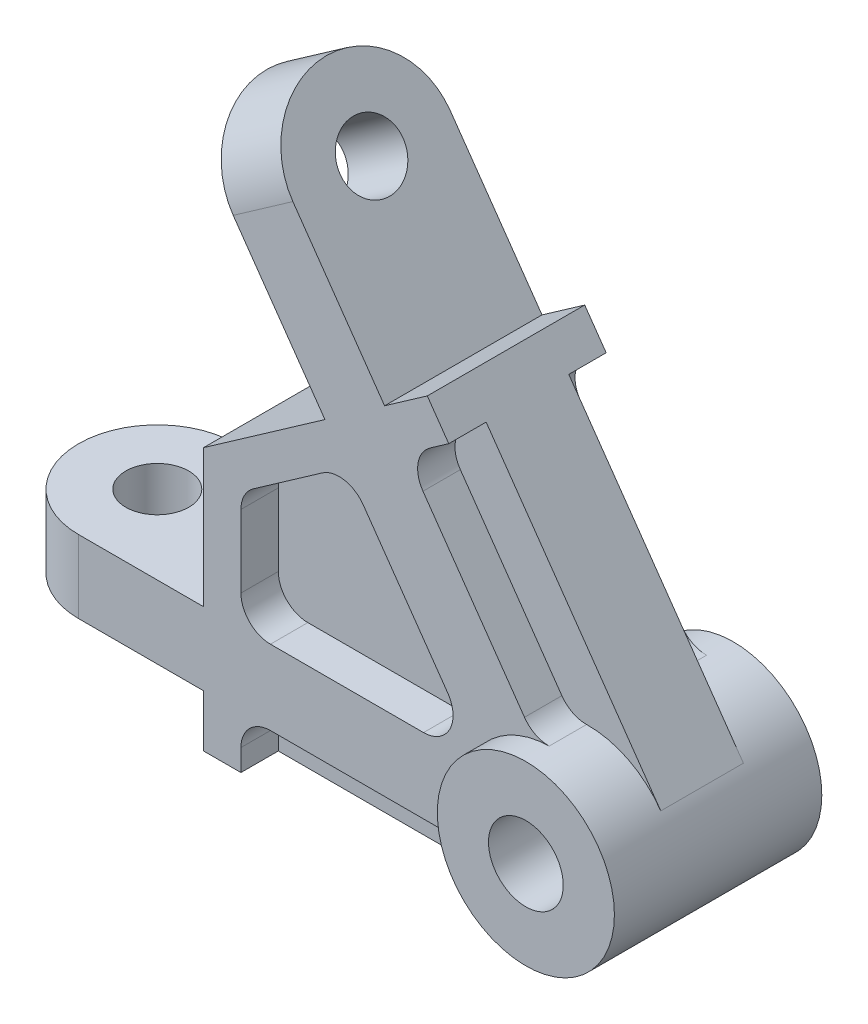
SolidWorks part; units mm, degrees
material "1060 Alloy"
ref_plane "Front Plane" through (0, 0, 0) normal (0, 0, 1) x (1, 0, 0)
ref_plane "Top Plane" through (0, 0, 0) normal (0, 1, 0) x (1, 0, 0)
ref_plane "Right Plane" through (0, 0, 0) normal (1, 0, 0) x (0, 0, -1)
sketch "Sketch2" plane through (0, 0, 0) normal (0, 1, 0) x (1, 0, 0)
  line L0 (0, 0) -> (-120, 0) construction
  line L1 (0, -20) -> (-120, -20)
  line L2 (0, 20) -> (-120, 20)
  line L3 (0, 30.8495) -> (0, -33.8206) construction
  line L4 (0, 20) -> (0, -20)
  circle A0 centre (-120, 0) radius 8
  arc A1 (-120, 20) -> (-120, -20) centre (-120, 0) ccw
  point P2 (0, 0)
  dimension "D3" = 16
  dimension "D1" = 40
  dimension "D2" = 120
extrude "Boss-Extrude1" add sketch "Sketch2" along normal mid plane 18.5
ref_plane "Plane1" through (0, 0, 0) normal (0.8192, 0.5736, 0) x (0.5736, -0.8192, 0)
sketch "Sketch3" plane through (0, 0, 0) normal (0.8192, 0.5736, 0) x (0.5736, -0.8192, 0)
  line L0 (0, 0) -> (-127.5, 0) construction
  line L1 (0, -20) -> (-127.5, -20)
  line L2 (0, 20) -> (-127.5, 20)
  line L3 (0, 20) -> (0, -20)
  arc A0 (127.5, -20) -> (127.5, 20) centre (127.5, 0) ccw
  arc A1 (-127.5, 20) -> (-127.5, -20) centre (-127.5, 0) ccw
  circle A2 centre (-127.5, 0) radius 8
  point P2 (0, 0)
  dimension "D2" = 16
  dimension "D1" = 40
  dimension "Achange" = 127.5
extrude "Boss-Extrude2" add sketch "Sketch3" along normal mid plane 18.5
sketch "Sketch5" plane through (0, 0, 0) normal (0, 0, 1) x (1, 0, 0)
  line L0 (0, -22.5) -> (-88.25, -22.5)
  line L1 (18.4309, 12.9055) -> (-31.3931, 84.0616)
  line L2 (-88.25, -22.5) -> (-88.25, 44.25)
  line L3 (-120, 9.25) -> (-17.7691, 9.25) construction
  line L4 (-88.25, 44.25) -> (-31.3931, 84.0616)
  line L5 (12.6187, -18.0213) -> (-12.6187, 18.0213) construction
  circle A0 centre (0, 0) radius 22.5
  dimension "D1" = 45
  dimension "D2" = 31.75
  dimension "D3" = 35
extrude "Boss-Extrude3" add sketch "Sketch5" along normal mid plane 40 contours A0 L1 L4 L2 L0 | A0
sketch "Sketch6" plane through (0, 0, 0) normal (0, 0, 1) x (1, 0, 0)
  circle A0 centre (0, 0) radius 9.5
  dimension "D1" = 19
extrude "Cut-Extrude1" cut sketch "Sketch6" against normal mid plane 40
sketch "Sketch7" plane through (0, 0, 20) normal (0, 0, 1) x (1, 0, 0)
  line L0 (18.4309, 12.9055) -> (-31.3931, 84.0616) construction
  line L1 (-36.7979, 68.6798) -> (-25.9442, 76.2797)
  line L2 (-36.7979, 68.6798) -> (-4.1873, 22.1069)
  line L3 (-42.2469, 76.4617) -> (-65.5538, 109.7475) construction
  line L4 (-51.9522, 58.0686) -> (-26.1829, 21.2662)
  line L5 (-57.4012, 65.8506) -> (-80.7082, 99.1363) construction
  line L6 (-26.1829, 21.2662) -> (-17.9441, 9.5)
  line L7 (0, 9.5) -> (-120, 9.5)
  line L8 (-36.7979, 9.5) -> (-78.75, 9.5)
  line L9 (0, -9.5) -> (-120, -9.5)
  line L10 (-20.3961, -9.5) -> (-78.75, -9.5)
  line L11 (-36.7979, 9.5) -> (-17.9441, 9.5)
  line L12 (-78.75, -22.5) -> (-78.75, -9.25)
  line L13 (-78.75, -22.5) -> (-78.75, -9.25)
  line L14 (-25.9442, 76.2797) -> (18.4309, 12.9055)
  line L15 (-78.75, -22.5) -> (0, -22.5)
  line L23 (-78.75, 9.25) -> (-78.75, 39.3046)
  line L24 (-78.75, 39.3046) -> (-51.9522, 58.0686)
  line L25 (-78.75, 9.25) -> (-78.75, 39.3046)
  line L26 (-78.75, 39.3046) -> (-51.9522, 58.0686)
  arc A0 (-20.3961, -9.5) -> (-4.1873, 22.1069) centre (0, 0) ccw
  arc A1 (0, -22.5) -> (18.4309, 12.9055) centre (0, 0) ccw construction
  dimension "D1" = 9.5
  dimension "D2" = 9.5
  dimension "D3" = 9.5
  dimension "D4" = 9.5
extrude "Cut-Extrude3" cut sketch "Sketch7" against normal blind 9.5 contours L26 L25 L8 L11 L6 L4 | A0 L5 L1 L2 | A0 L10 L13 L2
fillet "Fillet1" radius 7.5 8 edges at (-4.1873, 22.1069, 15.25) (-36.7979, 68.6798, 15.25) (-78.75, 9.5, 15.25) (-20.3961, -9.5, 15.25) (-78.75, 39.3046, 15.25) (-78.75, -9.5, 15.25) (-51.9522, 58.0686, 15.25) (-17.9441, 9.5, 15.25)
mirror "Mirror1" about plane through (0, 0, 0) normal (0, 0, 1) of "Fillet1", "Cut-Extrude3"
sketch "Sketch9" plane through (0, 0, 20) normal (0, 0, 1) x (1, 0, 0)
  circle A0 centre (0, 0) radius 22.5
  arc A1 (-18.5388, -12.75) -> (-0.416, 22.4962) centre (0, 0) ccw construction
  circle A2 centre (0, 0) radius 9.5
  circle A3 centre (0, 0) radius 9.5 construction
extrude "Boss-Extrude5" add sketch "Sketch9" along normal blind 6.35
mirror "Mirror2" about plane through (0, 0, 0) normal (0, 0, 1) of "Boss-Extrude5"
